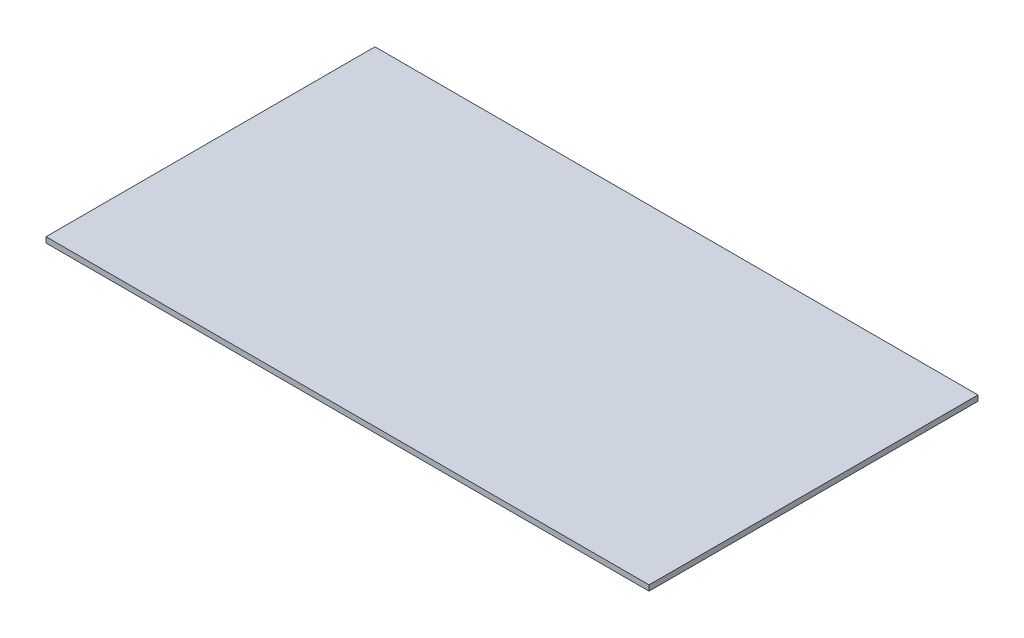
SolidWorks part; units mm, degrees
ref_plane "正面" through (0, 0, 0) normal (0, 0, 1) x (1, 0, 0)
ref_plane "平面" through (0, 0, 0) normal (0, 1, 0) x (1, 0, 0)
ref_plane "右側面" through (0, 0, 0) normal (1, 0, 0) x (0, 0, -1)
sketch "ｽｹｯﾁ1" plane through (0, 0, 0) normal (0, 1, 0) x (1, 0, 0)
  line L1 (-275, 150) -> (275, 150)
  line L2 (-275, 150) -> (-275, -150)
  line L3 (-275, -150) -> (275, -150)
  line L4 (275, 150) -> (275, -150)
  line L5 (-275, 150) -> (275, -150) construction
  line L6 (-275, -150) -> (275, 150) construction
  point P0 (0, 0)
  dimension "D1" = 300
  dimension "D2" = 550
extrude "ﾎﾞｽ - 押し出し1" add sketch "ｽｹｯﾁ1" along normal blind 5
